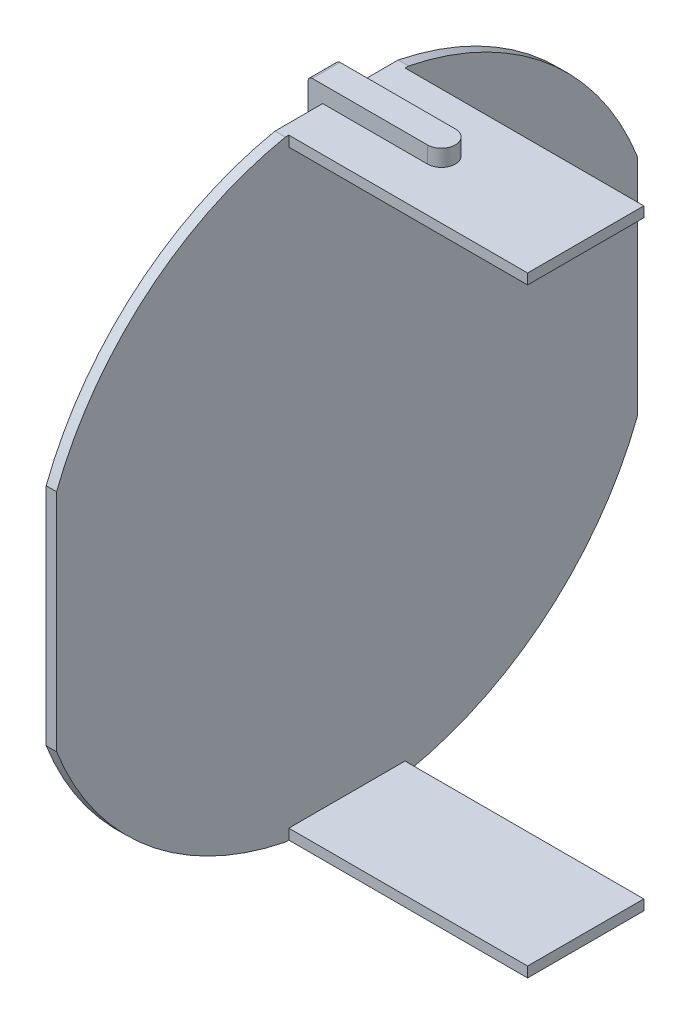
SolidWorks part; units mm, degrees
ref_plane "Plano frontal" through (0, 0, 0) normal (0, 0, 1) x (1, 0, 0)
ref_plane "Plano superior" through (0, 0, 0) normal (0, 1, 0) x (1, 0, 0)
ref_plane "Plano direito" through (0, 0, 0) normal (1, 0, 0) x (0, 0, -1)
sketch "Esboço1" plane through (0, 0, 0) normal (1, 0, 0) x (0, 0, -1)
  circle A0 centre (0, 0) radius 7.5
  dimension "D1" = 15
extrude "Ressalto-extrusão1" add sketch "Esboço1" along normal blind 6
sketch "Esboço2" plane through (0, 0, 0) normal (-1, 0, 0) x (0, 0, 1)
  line L0 (-1.5, 7.3518) -> (-1.5, 7.824)
  line L1 (-1.5, -7.3518) -> (1.5, -7.3518)
  line L3 (-1.5, 7.3518) -> (1.5, 7.3518)
  line L7 (-1.5, -7.824) -> (1.5, -7.824)
  line L8 (-1.5, -7.824) -> (-1.5, -7.3518)
  line L9 (-1.5, 7.824) -> (1.5, 7.824)
  line L10 (1.5, -7.824) -> (1.5, -7.3518)
  line L12 (-1.5, 7.824) -> (-1.4095, 7.3518) construction
  line L13 (1.5, 7.3518) -> (1.5, 7.824)
  line L14 (1.4095, 7.3518) -> (1.5, 7.824) construction
  dimension "D2" = 3
extrude "Corte-extrusão1" cut sketch "Esboço2" against normal blind 6
sketch "Esboço3" plane through (0, 0, 0) normal (-1, 0, 0) x (0, 0, 1)
  line L0 (-1.4834, 7.1018) -> (-1.4834, 7.3518)
  line L1 (-1.4834, -7.3518) -> (1.4834, -7.3518)
  line L2 (-1.4834, -7.3518) -> (-1.4834, -7.1018)
  line L3 (-1.4834, 7.3518) -> (1.4834, 7.3518)
  line L4 (1.4834, -7.3518) -> (1.4834, -7.1018)
  line L7 (-1.4834, -7.1018) -> (1.4834, -7.1018)
  line L9 (-1.4834, 7.1018) -> (1.4834, 7.1018)
  line L14 (1.4834, 7.1018) -> (1.4834, 7.3518)
  point P0 (0, 0)
  point P7 (0, 0)
  dimension "D1" = 0.25
extrude "Ressalto-extrusão2" add sketch "Esboço3" against normal blind 5.75
sketch "Esboço4" plane through (6, 0, 0) normal (1, 0, 0) x (0, 0, -1)
  line L0 (1.4834, 7.3518) -> (-1.4834, 7.3518) construction
  line L1 (-11.4049, -7.1018) -> (11.4049, -7.1018)
  line L2 (-11.4049, -7.1018) -> (-11.4049, 7.1018)
  line L3 (-11.4049, 7.1018) -> (11.4049, 7.1018)
  line L4 (11.4049, -7.1018) -> (11.4049, 7.1018)
  line L5 (-11.4049, -7.1018) -> (11.4049, 7.1018) construction
  line L6 (-11.4049, 7.1018) -> (11.4049, -7.1018) construction
  point P0 (0, 0)
  point P6 (0, 7.1018)
  dimension "D1" = 0.25
extrude "Corte-extrusão2" cut sketch "Esboço4" against normal blind 5.75
sketch "Esboço5" plane through (0.25, 0, 0) normal (1, 0, 0) x (0, 0, -1)
  line L0 (1.3994, 7.6253) -> (8.6501, 7.6253)
  line L2 (-1.3994, -7.6253) -> (-1.3994, 7.6253)
  line L4 (1.3994, -7.6253) -> (1.3994, 7.6253)
  line L7 (8.6501, 7.6253) -> (8.6501, -7.6253)
  line L8 (8.6501, -7.6253) -> (1.3994, -7.6253)
  line L9 (-1.3994, -7.6253) -> (-11.3829, -7.2066)
  line L10 (-11.3829, -7.2066) -> (-9.4876, 6.7879)
  line L11 (-9.4876, 6.7879) -> (-6.7107, 8)
  line L12 (-6.7107, 8) -> (-5.1657, 7.3939)
  line L13 (-5.1657, 7.3939) -> (-1.3994, 7.6253)
  point P0 (0, 0)
extrude "Corte-extrusão3" cut sketch "Esboço5" along normal blind 10.75
sketch "Esboço6" plane through (0, -7.3518, 0) normal (0, -1, 0) x (1, 0, 0)
  line L0 (-2.5435, 0) -> (2.5435, 0) construction
  line L1 (-2.5435, 0.322) -> (2.5435, 0.322)
  line L2 (-2.5435, -0.322) -> (2.5435, -0.322)
  arc A0 (-2.5435, 0.322) -> (-2.5435, -0.322) centre (-2.5435, 0) ccw
  arc A1 (2.5435, -0.322) -> (2.5435, 0.322) centre (2.5435, 0) ccw
  point P2 (0, 0)
extrude "Ressalto-extrusão3" add sketch "Esboço6" along normal blind 0.35
sketch "Esboço8" plane through (0, 0, 0) normal (-1, 0, 0) x (0, 0, 1)
  line L0 (0, -9.3057) -> (0, -5.398) construction
  line L1 (-0.322, -7.3518) -> (0.322, -7.3518) construction
  line L2 (-0.3143, -9.3057) -> (-0.3143, -5.398)
  line L3 (0.3143, -9.3057) -> (0.3143, -5.398)
  arc A0 (-0.3143, -9.3057) -> (0.3143, -9.3057) centre (0, -9.3057) ccw
  arc A1 (0.3143, -5.398) -> (-0.3143, -5.398) centre (0, -5.398) ccw
  point P5 (0, -7.3518)
extrude "Ressalto-extrusão4" add sketch "Esboço8" along normal blind 0.35
sketch "Esboço9" plane through (0, 0, -0.322) normal (0, 0, -1) x (-1, 0, 0)
  line L0 (0.35, -7.7018) -> (0.35, -4.8133)
  line L1 (0.35, -7.7018) -> (1.0832, -8.4351)
  line L2 (1.0832, -8.4351) -> (3.7017, -8.0685)
  line L3 (3.7017, -8.0685) -> (3.812, -6.7899)
  line L4 (3.812, -6.7899) -> (0.35, -4.8133)
extrude "Corte-extrusão5" cut sketch "Esboço9" against normal blind 6.35 and the other way blind 16
sketch "Esboço10" plane through (0, 0, -0.3143) normal (0, 0, -1) x (-1, 0, 0)
  line L0 (-0.1614, -7.7018) -> (0.8596, -7.7018)
  line L1 (0.35, -7.7018) -> (-2.5435, -7.7018) construction
  line L2 (0.8596, -7.7018) -> (0.8596, -10.4091)
  line L3 (0.8596, -10.4091) -> (-1.0967, -10.331)
  line L4 (-1.0967, -10.331) -> (-0.1614, -7.7018)
extrude "Corte-extrusão6" cut sketch "Esboço10" along normal blind 7.35 and the other way blind 13
fillet "Filete1" radius 0.1 1 edges at (-0.35, -7.7018, 0)
sketch "Esboço11" plane through (0, 7.3518, 0) normal (0, 1, 0) x (1, 0, 0)
  line L0 (-2.5254, 0) -> (2.5254, 0) construction
  line L1 (-2.5254, 0.3342) -> (2.5254, 0.3342)
  line L2 (-2.5254, -0.3342) -> (2.5254, -0.3342)
  arc A0 (-2.5254, 0.3342) -> (-2.5254, -0.3342) centre (-2.5254, 0) ccw
  arc A1 (2.5254, -0.3342) -> (2.5254, 0.3342) centre (2.5254, 0) ccw
  point P2 (0, 0)
extrude "Ressalto-extrusão5" add sketch "Esboço11" along normal blind 0.4
sketch "Esboço13" plane through (0, 7.7518, 0) normal (0, 1, 0) x (1, 0, 0)
  line L0 (-0.3499, -0.3342) -> (-0.3499, 0.5409)
  line L1 (-2.5254, -0.3342) -> (2.5254, -0.3342) construction
  line L2 (-0.3499, 0.5409) -> (-0.7645, 0.5728)
  line L3 (-0.7645, 0.5728) -> (-3.1343, 0.4177)
  line L4 (-3.1343, 0.4177) -> (-3.2316, -0.8475)
  line L5 (-3.2316, -0.8475) -> (0, -1.0131)
  line L6 (0, -1.4834) -> (0, -0.3342) construction
  line L7 (0, -1.0131) -> (-0.3499, -0.3342)
extrude "Corte-extrusão7" cut sketch "Esboço13" against normal blind 0.4
sketch "Esboço14" plane through (0, 7.3518, 0) normal (0, -1, 0) x (1, 0, 0)
  line L0 (0, -0.3342) -> (-0.3499, -0.3342)
  line L1 (-0.3499, -0.3342) -> (-0.3499, 0.3342)
  line L2 (-0.3499, 0.3342) -> (0, 0.3342)
  line L3 (0, 0.3342) -> (0, -0.3342)
extrude "Ressalto-extrusão6" add sketch "Esboço14" along normal blind 2.4
fillet "Filete2" radius 0.1 1 edges at (-0.3499, 7.7518, 0)
sketch "Esboço15" plane through (-0.3499, 0, 0) normal (-1, 0, 0) x (0, 0, 1)
  line L0 (-0.3342, 4.9518) -> (-0.3342, 7.3518) construction
  line L1 (0.3342, 4.9518) -> (0.3342, 7.3518) construction
  line L2 (-0.3342, 5.1814) -> (-0.7407, 5.1814)
  line L3 (-0.7407, 5.1814) -> (-0.5374, 4.7156)
  line L4 (-0.5374, 4.7156) -> (0.581, 4.5268)
  line L5 (0.581, 4.5268) -> (0.8579, 4.9471)
  line L6 (0.8579, 4.9471) -> (0.3342, 5.1814)
  arc A0 (-0.3342, 5.1814) -> (0.3342, 5.1814) centre (0, 5.3027) ccw
extrude "Corte-extrusão9" cut sketch "Esboço15" against normal blind 0.35
sketch "Esboço19" plane through (0.25, 0, 0) normal (1, 0, 0) x (0, 0, -1)
  line L0 (-6.9927, 8.1889) -> (-12.7213, -3.8018)
  line L2 (-6.9927, -8.1889) -> (-6.9927, 8.1889)
  line L4 (6.9927, -8.1889) -> (6.9927, 8.1889)
  line L7 (-12.7213, -3.8018) -> (-6.9927, -8.1889)
  line L8 (6.9927, -8.1889) -> (11.0746, 2.1935)
  line L9 (11.0746, 2.1935) -> (6.9927, 8.1889)
  point P0 (0, 0)
extrude "Corte-extrusão10" cut sketch "Esboço19" against normal blind 7.35 and the other way blind 15
